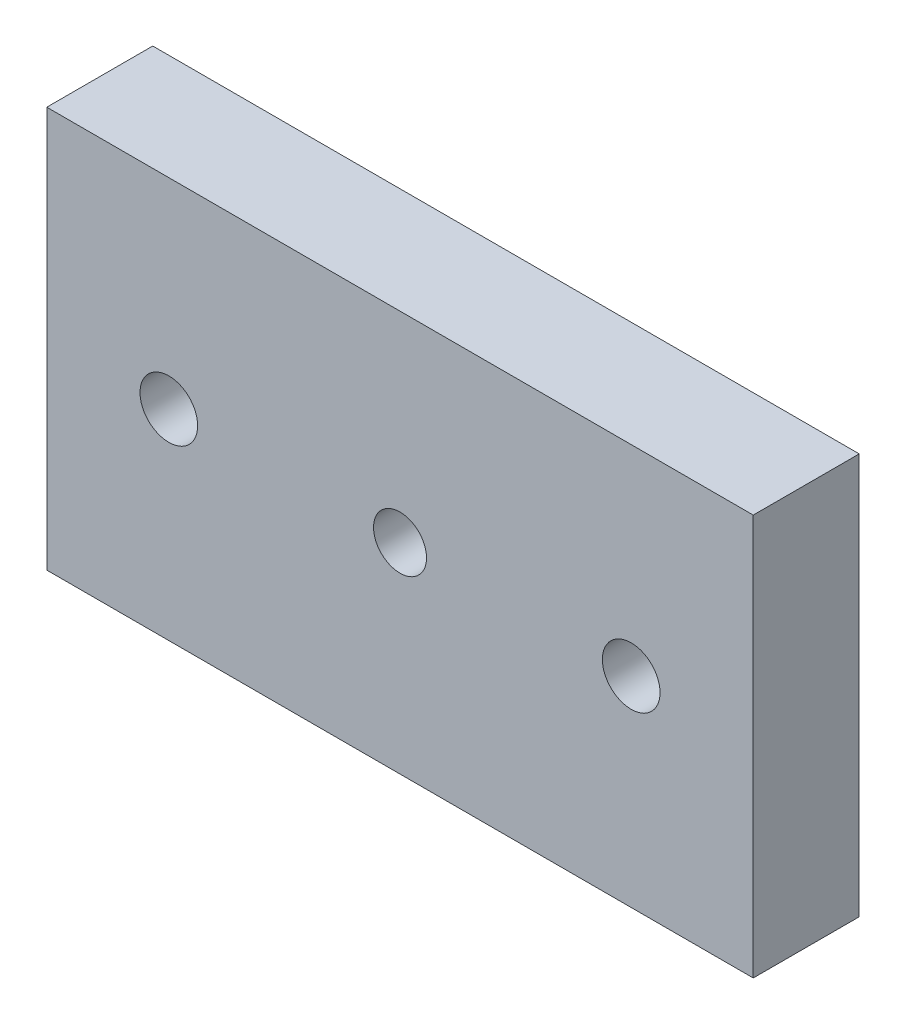
SolidWorks part; units mm, degrees
ref_plane "Front Plane" through (0, 0, 0) normal (0, 0, 1) x (1, 0, 0)
ref_plane "Top Plane" through (0, 0, 0) normal (0, 1, 0) x (1, 0, 0)
ref_plane "Right Plane" through (0, 0, 0) normal (1, 0, 0) x (0, 0, -1)
sketch "Sketch1" plane through (0, 0, 0) normal (0, 0, 1) x (1, 0, 0)
  line L1 (-20, 11.35) -> (20, 11.35)
  line L2 (-20, 11.35) -> (-20, -11.35)
  line L3 (-20, -11.35) -> (20, -11.35)
  line L4 (20, 11.35) -> (20, -11.35)
  line L5 (-20, 11.35) -> (20, -11.35) construction
  line L6 (-20, -11.35) -> (20, 11.35) construction
  point P0 (0, 0)
  dimension "D1" = 22.7
  dimension "D2" = 40
extrude "Boss-Extrude1" add sketch "Sketch1" against normal blind 6
hole_wizard "#4 Clearance Hole1" positions "Sketch2" profile "Sketch3" hole size "#4" standard "ANSI Inch" end condition through all
sketch "Sketch2" plane through (0, 0, 0) normal (0, 0, 1) x (1, 0, 0)
  point P0 (-13.09, 0)
  point P2 (13.09, 0)
  dimension "D1" = 26.18
  dimension "D2" = 13.09
sketch "Sketch3" plane through (-13.09, 0, 0) normal (1, 0, 0) x (0, -1, 0)
  line L0 (0, 0) -> (0, 6)
  line L1 (0, 6) -> (1.6319, 6)
  line L2 (1.6319, 6) -> (1.6319, 0)
  line L5 (1.6319, 0) -> (0, 0)
  line L11 (0, -6.35) -> (0, 107.95) construction
  dimension "Thru Hole Dia." = 3.2639
  dimension "Thru Hole Depth" = 6
hole_wizard "Ø3.0mm Dowel Hole1" positions "Sketch4" profile "Sketch5" hole size "Ø3.0" standard "ANSI Metric" end condition through all
sketch "Sketch4" plane through (0, 0, 0) normal (0, 0, 1) x (1, 0, 0)
  point P0 (0, 0)
sketch "Sketch5" plane through (0, 0, 0) normal (1, 0, 0) x (0, -1, 0)
  line L0 (0, 0) -> (0, 6)
  line L1 (0, 6) -> (1.5, 6)
  line L2 (1.5, 6) -> (1.5, 0)
  line L5 (1.5, 0) -> (0, 0)
  line L11 (0, -6.35) -> (0, 107.95) construction
  dimension "Thru Hole Dia." = 3
  dimension "Thru Hole Depth" = 6
equation "\"D2@Sketch2\"=\"D1@Sketch2\"/2"
